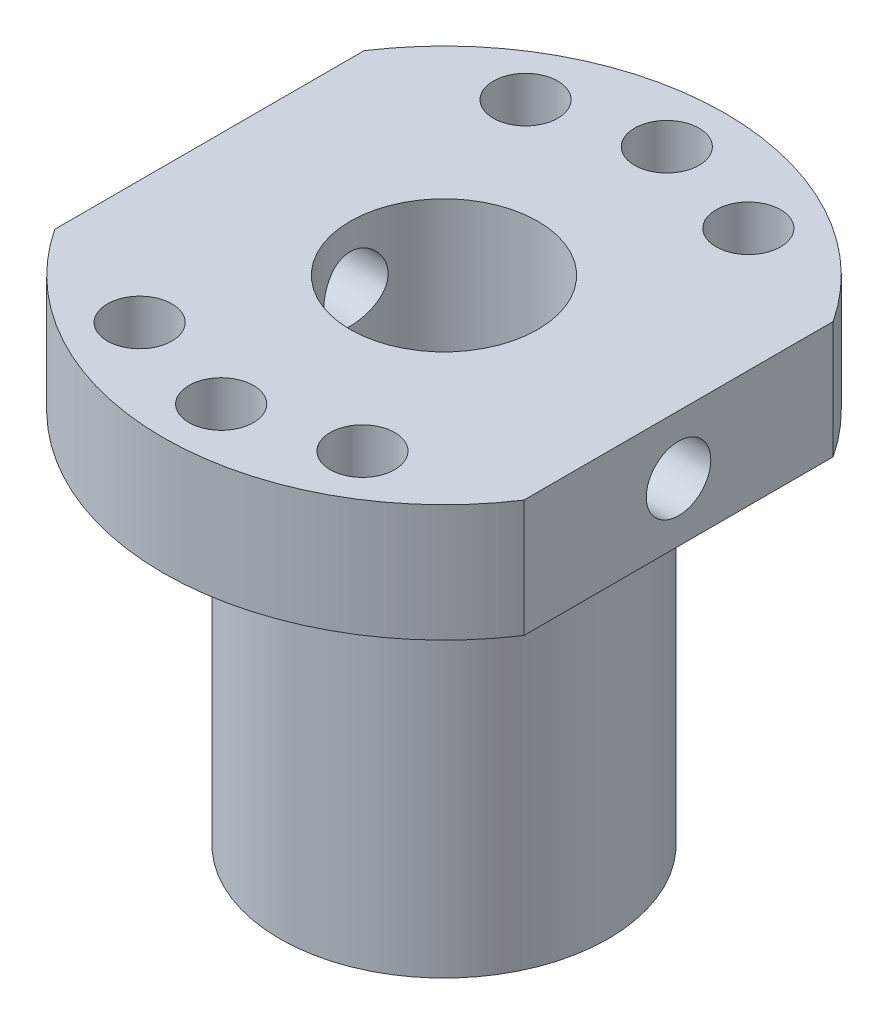
SolidWorks part; units mm, degrees
ref_plane "Plan de face" through (0, 0, 0) normal (0, 0, 1) x (1, 0, 0)
ref_plane "Plan de dessus" through (0, 0, 0) normal (0, 1, 0) x (1, 0, 0)
ref_plane "Plan de droite" through (0, 0, 0) normal (1, 0, 0) x (0, 0, -1)
sketch "Sketch1" plane through (0, 0, 0) normal (0, 1, 0) x (1, 0, 0)
  circle A0 centre (0, 0) radius 14
  dimension "D1" = 28
extrude "Boss-Extrude1" add sketch "Sketch1" along normal blind 32
sketch "Sketch5" plane through (0, 32, 0) normal (0, 1, 0) x (-1, 0, 0)
  line L2 (-20, 13.1868) -> (-20, -13.1868)
  line L4 (20, 13.1868) -> (20, -13.1868)
  arc A0 (20, 13.1868) -> (-20, 13.1868) centre (0, 0) ccw
  arc A1 (-20, -13.1868) -> (20, -13.1868) centre (0, 0) ccw
extrude "Boss-Extrude2" add sketch "Sketch5" along normal blind 10
sketch "Sketch6" plane through (0, 42, 0) normal (0, 1, 0) x (-1, 0, 0)
  circle A0 centre (0, 0) radius 8
extrude "Cut-Extrude1" cut sketch "Sketch6" against normal through all
sketch "Sketch8" plane through (0, 42, 0) normal (0, 1, 0) x (-1, 0, 0)
  circle A0 centre (0, 0) radius 19
  circle A1 centre (0, 19) radius 2.75
  circle A2 centre (9.5, 16.4545) radius 2.75
  circle A3 centre (16.4545, 9.5) radius 2.75 [skipped]
  circle A4 centre (19, 0) radius 2.75 [skipped]
  circle A5 centre (16.4545, -9.5) radius 2.75 [skipped]
  circle A6 centre (9.5, -16.4545) radius 2.75
  circle A7 centre (0, -19) radius 2.75
  circle A8 centre (-9.5, -16.4545) radius 2.75
  circle A9 centre (-16.4545, -9.5) radius 2.75 [skipped]
  circle A10 centre (-19, 0) radius 2.75 [skipped]
  circle A11 centre (-16.4545, 9.5) radius 2.75 [skipped]
  circle A12 centre (-9.5, 16.4545) radius 2.75
  dimension "D1" = 12
extrude "Cut-Extrude2" cut sketch "Sketch8" against normal through all contours A1 | A2 | A12 | A8 | A7 | A6
sketch "Sketch9" plane through (20, 0, 0) normal (1, 0, 0) x (0, 0, -1)
  circle A0 centre (0, 37) radius 2.75
extrude "Cut-Extrude3" cut sketch "Sketch9" against normal through all
